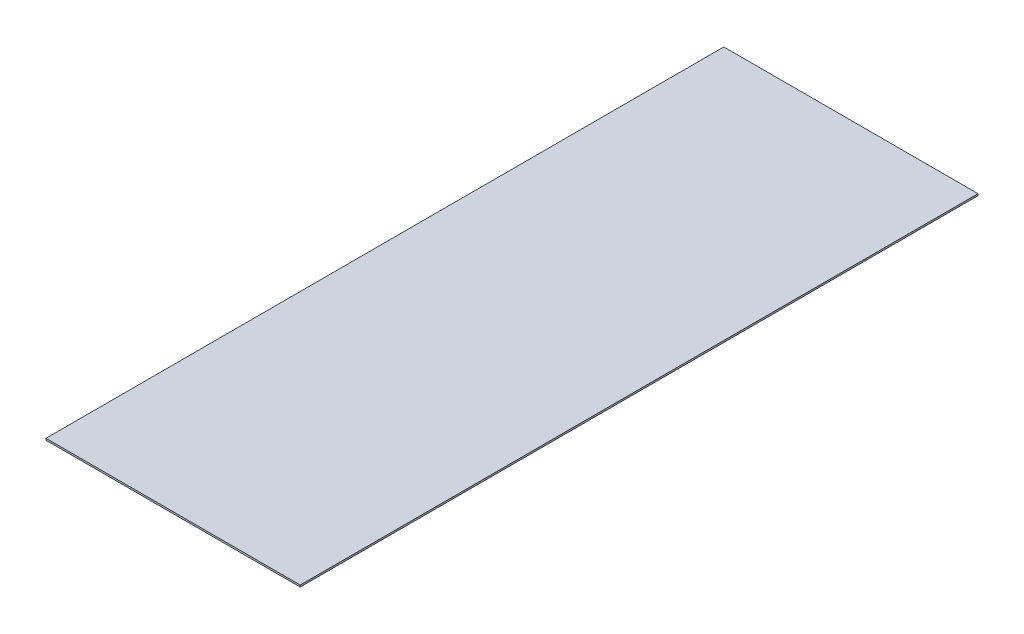
SolidWorks part; units mm, degrees
material "ASTM A36 Acero"
ref_plane "Alzado" through (0, 0, 0) normal (0, 0, 1) x (1, 0, 0)
ref_plane "Planta" through (0, 0, 0) normal (0, 1, 0) x (1, 0, 0)
ref_plane "Vista lateral" through (0, 0, 0) normal (1, 0, 0) x (0, 0, -1)
sketch "Croquis1" plane through (0, 0, 0) normal (0, 1, 0) x (1, 0, 0)
  line L1 (-457.2, -1219.2) -> (457.2, -1219.2)
  line L2 (-457.2, -1219.2) -> (-457.2, 1219.2)
  line L3 (-457.2, 1219.2) -> (457.2, 1219.2)
  line L4 (457.2, -1219.2) -> (457.2, 1219.2)
  line L5 (-457.2, -1219.2) -> (457.2, 1219.2) construction
  line L6 (-457.2, 1219.2) -> (457.2, -1219.2) construction
  point P0 (0, 0)
  dimension "D1" = 2438.4
  dimension "D2" = 914.4
extrude "Saliente-Extruir1" add sketch "Croquis1" along normal blind 6.4
